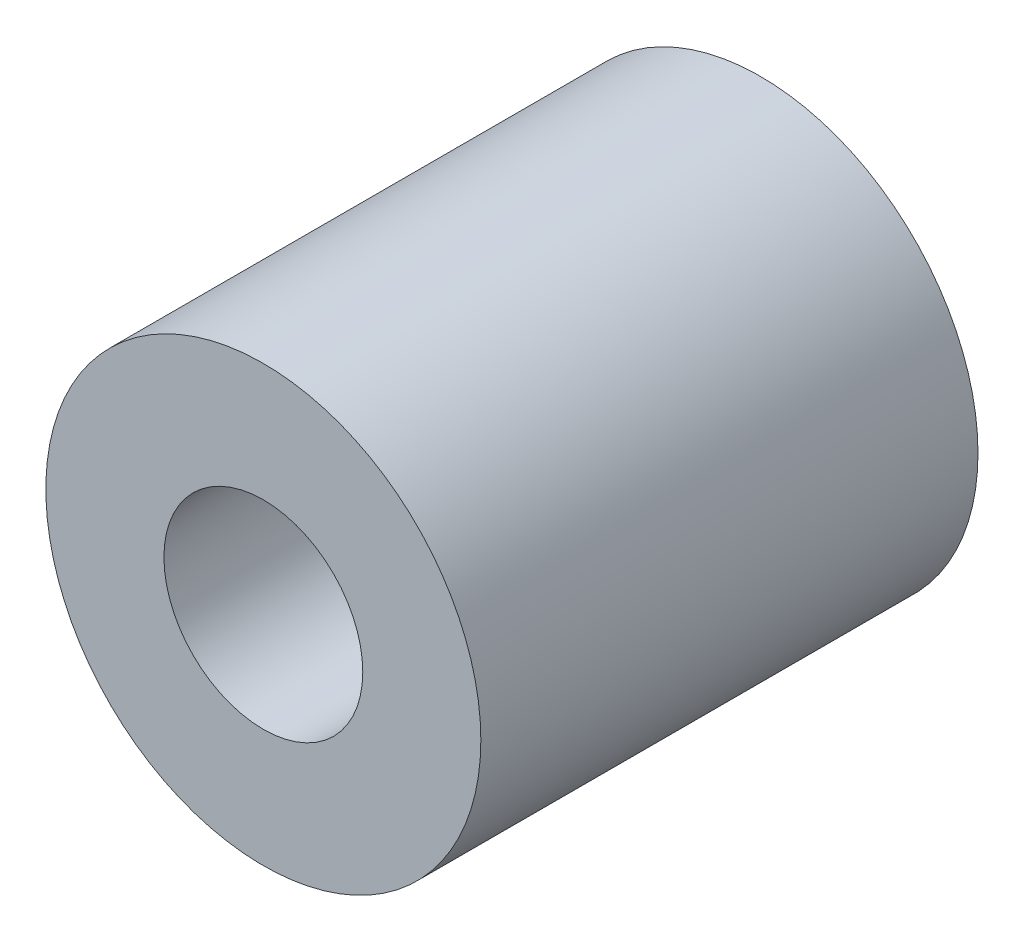
SolidWorks part; units mm, degrees
ref_plane "正面" through (0, 0, 0) normal (0, 0, 1) x (1, 0, 0)
ref_plane "平面" through (0, 0, 0) normal (0, 1, 0) x (1, 0, 0)
ref_plane "右側面" through (0, 0, 0) normal (1, 0, 0) x (0, 0, -1)
sketch "ｽｹｯﾁ1" plane through (0, 0, 0) normal (0, 0, 1) x (1, 0, 0)
  circle A0 centre (0, 0) radius 3.5
  circle A1 centre (0, 0) radius 1.6
  dimension "D1" = 7
  dimension "D2" = 3.2
extrude "ﾎﾞｽ - 押し出し1" add sketch "ｽｹｯﾁ1" along normal blind 8
